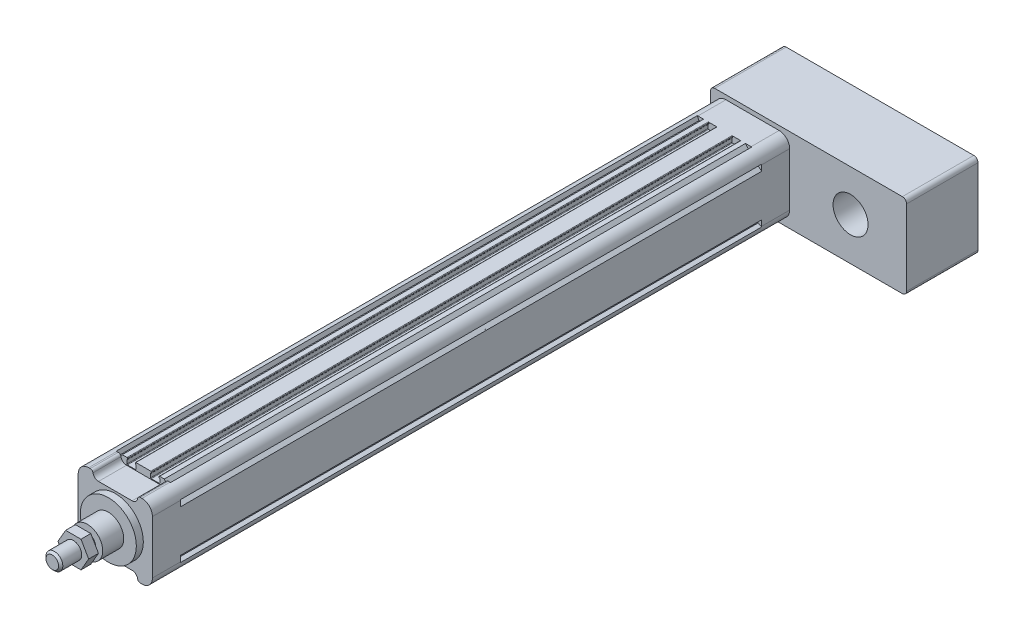
SolidWorks part; units mm, degrees
ref_plane "Front" through (0, 0, 0) normal (0, 0, 1) x (1, 0, 0)
ref_plane "Top" through (0, 0, 0) normal (0, 1, 0) x (1, 0, 0)
ref_plane "Right" through (0, 0, 0) normal (1, 0, 0) x (0, 0, -1)
sketch "草图1" plane through (0, 0, 0) normal (0, 0, 1) x (1, 0, 0)
  line L0 (19.7737, 3) -> (23.3, 3)
  line L1 (23.3, 3) -> (23.3, -3)
  line L2 (23.3, -3) -> (19.7737, -3)
  line L3 (-19.7737, -3) -> (-23.3, -3)
  line L4 (-23.3, -3) -> (-23.3, 3)
  line L5 (-23.3, 3) -> (-19.7737, 3)
  line L6 (-18.2, 24) -> (-19.4434, 26.4869)
  line L7 (-26.4869, 19.4434) -> (-24, 18.2)
  line L8 (-24, 18.2) -> (-24, 17.1)
  line L9 (-24, 17.1) -> (-26.5, 15)
  line L10 (-26.5, 15) -> (-26.5, -15)
  line L11 (-26.5, -15) -> (-24, -17.1)
  line L12 (-24, -17.1) -> (-24, -18.2)
  line L13 (-24, -18.2) -> (-26.4869, -19.4434)
  line L14 (-19.4434, -26.4869) -> (-18.2, -24)
  line L15 (-18.2, -24) -> (-17.1, -24)
  line L16 (-17.1, -24) -> (-15, -26.5)
  line L17 (-15, -26.5) -> (-11.65, -26.5)
  line L18 (-11.25, -26.1) -> (-11.25, -25.6)
  line L19 (-11.65, -25.2) -> (-11.75, -25.2)
  line L20 (-11.75, -25.2) -> (-11.75, -22.4)
  line L21 (-11.35, -22) -> (-5.65, -22)
  line L22 (-5.25, -22.4) -> (-5.25, -25.2)
  line L23 (-5.25, -25.2) -> (-5.35, -25.2)
  line L24 (-5.75, -25.6) -> (-5.75, -26.1)
  line L25 (-5.35, -26.5) -> (5.35, -26.5)
  line L26 (5.75, -26.1) -> (5.75, -25.6)
  line L27 (5.35, -25.2) -> (5.25, -25.2)
  line L28 (5.25, -25.2) -> (5.25, -22.4)
  line L29 (5.65, -22) -> (11.35, -22)
  line L30 (11.75, -22.4) -> (11.75, -25.2)
  line L31 (11.75, -25.2) -> (11.65, -25.2)
  line L32 (11.25, -25.6) -> (11.25, -26.1)
  line L33 (11.65, -26.5) -> (15, -26.5)
  line L34 (15, -26.5) -> (17.1, -24)
  line L35 (17.1, -24) -> (18.2, -24)
  line L36 (18.2, -24) -> (19.4434, -26.4869)
  line L37 (26.4869, -19.4434) -> (24, -18.2)
  line L38 (24, -18.2) -> (24, -17.1)
  line L39 (24, -17.1) -> (26.5, -15)
  line L40 (26.5, -15) -> (26.5, 15)
  line L41 (26.5, 15) -> (24, 17.1)
  line L42 (24, 17.1) -> (24, 18.2)
  line L43 (24, 18.2) -> (26.4869, 19.4434)
  line L44 (19.4434, 26.4869) -> (18.2, 24)
  line L45 (18.2, 24) -> (17.1, 24)
  line L46 (17.1, 24) -> (15, 26.5)
  line L47 (15, 26.5) -> (11.65, 26.5)
  line L48 (11.25, 26.1) -> (11.25, 25.6)
  line L49 (11.65, 25.2) -> (11.75, 25.2)
  line L50 (11.75, 25.2) -> (11.75, 22.4)
  line L51 (11.35, 22) -> (5.65, 22)
  line L52 (5.25, 22.4) -> (5.25, 25.2)
  line L53 (5.25, 25.2) -> (5.35, 25.2)
  line L54 (5.75, 25.6) -> (5.75, 26.1)
  line L55 (5.35, 26.5) -> (-5.35, 26.5)
  line L56 (-5.75, 26.1) -> (-5.75, 25.6)
  line L57 (-5.35, 25.2) -> (-5.25, 25.2)
  line L58 (-5.25, 25.2) -> (-5.25, 22.4)
  line L59 (-5.65, 22) -> (-11.35, 22)
  line L60 (-11.75, 22.4) -> (-11.75, 25.2)
  line L61 (-11.75, 25.2) -> (-11.65, 25.2)
  line L62 (-11.25, 25.6) -> (-11.25, 26.1)
  line L63 (-11.65, 26.5) -> (-15, 26.5)
  line L64 (-15, 26.5) -> (-17.1, 24)
  line L65 (-17.1, 24) -> (-18.2, 24)
  arc A0 (19.7737, 3) -> (-19.7737, 3) centre (0, 0) ccw
  arc A1 (-19.7737, -3) -> (19.7737, -3) centre (0, 0) ccw
  circle A2 centre (19, 19) radius 2.1
  circle A3 centre (19, -19) radius 2.1
  circle A4 centre (-19, -19) radius 2.1
  circle A5 centre (-19, 19) radius 2.1
  arc A6 (-19.4434, 26.4869) -> (-26.4869, 19.4434) centre (-19, 19) ccw
  arc A7 (-26.4869, -19.4434) -> (-19.4434, -26.4869) centre (-19, -19) ccw
  arc A8 (-11.65, -26.5) -> (-11.25, -26.1) centre (-11.65, -26.1) ccw
  arc A9 (-11.25, -25.6) -> (-11.65, -25.2) centre (-11.65, -25.6) ccw
  arc A10 (-11.35, -22) -> (-11.75, -22.4) centre (-11.35, -22.4) ccw
  arc A11 (-5.25, -22.4) -> (-5.65, -22) centre (-5.65, -22.4) ccw
  arc A12 (-5.35, -25.2) -> (-5.75, -25.6) centre (-5.35, -25.6) ccw
  arc A13 (-5.75, -26.1) -> (-5.35, -26.5) centre (-5.35, -26.1) ccw
  arc A14 (5.35, -26.5) -> (5.75, -26.1) centre (5.35, -26.1) ccw
  arc A15 (5.75, -25.6) -> (5.35, -25.2) centre (5.35, -25.6) ccw
  arc A16 (5.65, -22) -> (5.25, -22.4) centre (5.65, -22.4) ccw
  arc A17 (11.75, -22.4) -> (11.35, -22) centre (11.35, -22.4) ccw
  arc A18 (11.65, -25.2) -> (11.25, -25.6) centre (11.65, -25.6) ccw
  arc A19 (11.25, -26.1) -> (11.65, -26.5) centre (11.65, -26.1) ccw
  arc A20 (19.4434, -26.4869) -> (26.4869, -19.4434) centre (19, -19) ccw
  arc A21 (26.4869, 19.4434) -> (19.4434, 26.4869) centre (19, 19) ccw
  arc A22 (11.65, 26.5) -> (11.25, 26.1) centre (11.65, 26.1) ccw
  arc A23 (11.25, 25.6) -> (11.65, 25.2) centre (11.65, 25.6) ccw
  arc A24 (11.35, 22) -> (11.75, 22.4) centre (11.35, 22.4) ccw
  arc A25 (5.25, 22.4) -> (5.65, 22) centre (5.65, 22.4) ccw
  arc A26 (5.35, 25.2) -> (5.75, 25.6) centre (5.35, 25.6) ccw
  arc A27 (5.75, 26.1) -> (5.35, 26.5) centre (5.35, 26.1) ccw
  arc A28 (-5.35, 26.5) -> (-5.75, 26.1) centre (-5.35, 26.1) ccw
  arc A29 (-5.75, 25.6) -> (-5.35, 25.2) centre (-5.35, 25.6) ccw
  arc A30 (-5.65, 22) -> (-5.25, 22.4) centre (-5.65, 22.4) ccw
  arc A31 (-11.75, 22.4) -> (-11.35, 22) centre (-11.35, 22.4) ccw
  arc A32 (-11.65, 25.2) -> (-11.25, 25.6) centre (-11.65, 25.6) ccw
  arc A33 (-11.25, 26.1) -> (-11.65, 26.5) centre (-11.65, 26.1) ccw
extrude "凸台-拉伸1" add sketch "草图1" along normal blind 415
sketch "草图6" plane through (0, 0, 415) normal (0, 0, 1) x (1, 0, 0)
  line L0 (0, 0) -> (19, 0) construction
  line L2 (-26.5, -19) -> (-26.5, 19)
  line L3 (-19, 26.5) -> (-17.9161, 26.5)
  line L4 (26.5, -19) -> (26.5, 19)
  line L5 (-26.5, -26.5) -> (26.5, 26.5) construction
  line L6 (-26.5, 26.5) -> (26.5, -26.5) construction
  line L7 (-12, 21.5) -> (12, 21.5)
  line L9 (19, 26.5) -> (17.9161, 26.5)
  line L10 (19, -26.5) -> (17.9161, -26.5)
  line L11 (-12, -21.5) -> (12, -21.5)
  line L12 (-19, -26.5) -> (-17.9161, -26.5)
  arc A0 (12, 21.5) -> (15.9441, 24.8333) centre (12, 25.5) ccw
  arc A1 (-15.9441, 24.8333) -> (-12, 21.5) centre (-12, 25.5) ccw
  arc A2 (-15.9441, 24.8333) -> (-17.9161, 26.5) centre (-17.9161, 24.5) ccw
  arc A3 (15.9441, 24.8333) -> (17.9161, 26.5) centre (17.9161, 24.5) cw
  arc A4 (-26.5, -19) -> (-19, -26.5) centre (-19, -19) ccw
  arc A5 (19, -26.5) -> (26.5, -19) centre (19, -19) ccw
  arc A6 (26.5, 19) -> (19, 26.5) centre (19, 19) ccw
  arc A7 (-26.5, 19) -> (-19, 26.5) centre (-19, 19) cw
  arc A8 (15.9441, -24.8333) -> (17.9161, -26.5) centre (17.9161, -24.5) ccw
  arc A9 (12, -21.5) -> (15.9441, -24.8333) centre (12, -25.5) cw
  arc A10 (-15.9441, -24.8333) -> (-12, -21.5) centre (-12, -25.5) cw
  arc A11 (-15.9441, -24.8333) -> (-17.9161, -26.5) centre (-17.9161, -24.5) cw
  point P0 (0, 0)
  point P9 (0, 21.5)
  point P13 (20, 20.8461)
  point P16 (-12, 20.8461)
  dimension "D5" = 4
  dimension "D6" = 2
  dimension "D7" = 2
  dimension "D9" = 7.5
  dimension "D1" = 53
  dimension "D2" = 53
  dimension "D3" = 26.5
  dimension "D4" = 24
  dimension "D8" = 5
extrude "凸台-拉伸2" add sketch "草图6" along normal blind 20
sketch "草图7" plane through (0, 0, 435) normal (0, 0, 1) x (1, 0, 0)
  circle A0 centre (0, 0) radius 20
  dimension "D1" = 40
extrude "凸台-拉伸3" add sketch "草图7" along normal blind 5
sketch "草图9" plane through (0, 0, 440) normal (0, 0, 1) x (1, 0, 0)
  circle A0 centre (0, 0) radius 11
  dimension "D1" = 22
extrude "凸台-拉伸4" add sketch "草图9" along normal blind 15
sketch "草图10" plane through (0, 0, 455) normal (0, 0, 1) x (1, 0, 0)
  circle A0 centre (0, 0) radius 6
  dimension "D1" = 12
extrude "凸台-拉伸5" add sketch "草图10" along normal blind 25
sketch "草图11" plane through (0, 0, 0) normal (0, 0, -1) x (-1, 0, 0)
  line L1 (-19, -26.5) -> (19, -26.5)
  line L2 (-26.5, -19) -> (-26.5, 19)
  line L3 (-19, 26.5) -> (19, 26.5)
  line L4 (26.5, -19) -> (26.5, 19)
  line L5 (-26.5, -26.5) -> (26.5, 26.5) construction
  line L6 (-26.5, 26.5) -> (26.5, -26.5) construction
  arc A0 (-26.5, -19) -> (-19, -26.5) centre (-19, -19) ccw
  arc A1 (19, -26.5) -> (26.5, -19) centre (19, -19) ccw
  arc A2 (26.5, 19) -> (19, 26.5) centre (19, 19) ccw
  arc A3 (-26.5, 19) -> (-19, 26.5) centre (-19, 19) cw
  point P0 (0, 0)
  dimension "D3" = 7.5
  dimension "D1" = 53
  dimension "D2" = 53
extrude "凸台-拉伸6" add sketch "草图11" along normal blind 20
sketch "草图12" plane through (0, 0, -20) normal (0, 0, -1) x (-1, 0, 0)
  line L1 (-107, -30.4042) -> (27, -30.4042)
  line L2 (-110, -27.4042) -> (-110, 26.5958)
  line L3 (-107, 29.5958) -> (27, 29.5958)
  line L4 (30, -27.4042) -> (30, 26.5958)
  line L5 (-110, -30.4042) -> (30, 29.5958) construction
  line L6 (-110, 29.5958) -> (30, -30.4042) construction
  arc A0 (27, 29.5958) -> (30, 26.5958) centre (27, 26.5958) cw
  arc A1 (30, -27.4042) -> (27, -30.4042) centre (27, -27.4042) cw
  arc A2 (-110, -27.4042) -> (-107, -30.4042) centre (-107, -27.4042) ccw
  arc A3 (-110, 26.5958) -> (-107, 29.5958) centre (-107, 26.5958) cw
  point P0 (-40, -0.4042)
  dimension "D4" = 3
  dimension "D1" = 60
  dimension "D2" = 140
  dimension "D3" = 30
extrude "凸台-拉伸7" add sketch "草图12" along normal blind 51
sketch "草图13" plane through (0, 0, -20) normal (0, 0, 1) x (1, 0, 0)
  circle A0 centre (70, 0) radius 12.5
  dimension "D2" = 25
  dimension "D1" = 70
extrude "切除-拉伸2" cut sketch "草图13" against normal blind 30
hole_wizard "M6 螺纹孔1" positions "草图14" profile "草图15" tap size "M6" standard "GB"
sketch "草图14" plane through (0, 0, -71) normal (0, 0, -1) x (-1, 0, 0)
  line L0 (30, -27.4042) -> (30, 26.5958) construction
  point P0 (19, -19)
  dimension "D1" = 11
  dimension "D2" = 19
sketch "草图15" plane through (-19, -19, -71) normal (1, 0, 0) x (0, 1, 0)
  line L0 (0, 0) -> (0, 16.5022)
  line L1 (0, 16.5022) -> (2.5, 15)
  line L2 (2.5, 15) -> (2.5, 0)
  line L5 (2.5, 0) -> (0, 0)
  line L10 (0, 16.5022) -> (-2.5, 15) construction
  line L11 (0, -6.35) -> (0, 107.95) construction
  dimension "螺纹孔钻头直径" = 5
  dimension "螺纹孔钻头深度" = 15
  dimension "导头角度" = 118
cosmetic thread "孔螺蚊线4" parameters "D1"=12, "D2"=6
pattern_linear "阵列(线性)1" count 2 spacing 38 along (0, 1, 0) count 2 spacing 38 along (1, 0, 0) of "M6 螺纹孔1"
hole_wizard "M6 螺纹孔2" positions "草图16" profile "草图17" tap size "M6" standard "GB"
sketch "草图16" plane through (0, 0, -71) normal (0, 0, -1) x (-1, 0, 0)
  circle A1 centre (-19, 19) radius 2.5 construction
  circle A2 centre (-19, -19) radius 2.5 construction
  point P0 (-84, -19)
  point P2 (-84, 19)
  dimension "D3" = 65
  dimension "D1" = 19
  dimension "D2" = 19
  dimension "D4" = 65
sketch "草图17" plane through (84, -19, -71) normal (1, 0, 0) x (0, 1, 0)
  line L0 (0, 0) -> (0, 16.5022)
  line L1 (0, 16.5022) -> (2.5, 15)
  line L2 (2.5, 15) -> (2.5, 0)
  line L5 (2.5, 0) -> (0, 0)
  line L10 (0, 16.5022) -> (-2.5, 15) construction
  line L11 (0, -6.35) -> (0, 107.95) construction
  dimension "螺纹孔钻头直径" = 5
  dimension "螺纹孔钻头深度" = 15
  dimension "导头角度" = 118
cosmetic thread "孔螺蚊线5" parameters "D1"=12, "D2"=6
cosmetic thread "孔螺蚊线6" parameters "D1"=12, "D2"=6
hole_wizard "M6 螺纹孔3" positions "草图19" profile "草图20" tap size "M6" standard "GB"
sketch "草图19" plane through (-26.5, 0, 0) normal (-1, 0, 0) x (0, 0, 1)
  line L0 (435, 19) -> (435, -19) construction
  point P0 (425, 11)
  point P2 (425, -11)
  dimension "D1" = 10
  dimension "D2" = 10
  dimension "D3" = 22
  dimension "D4" = 11
sketch "草图20" plane through (-26.5, 11, 425) normal (0, 1, 0) x (0, 0, 1)
  line L0 (0, 0) -> (0, 16.5022)
  line L1 (0, 16.5022) -> (2.5, 15)
  line L2 (2.5, 15) -> (2.5, 0)
  line L5 (2.5, 0) -> (0, 0)
  line L10 (0, 16.5022) -> (-2.5, 15) construction
  line L11 (0, -6.35) -> (0, 107.95) construction
  dimension "螺纹孔钻头直径" = 5
  dimension "螺纹孔钻头深度" = 15
  dimension "导头角度" = 118
cosmetic thread "孔螺蚊线7" parameters "D1"=12, "D2"=6
cosmetic thread "孔螺蚊线8" parameters "D1"=12, "D2"=6
hole_wizard "M6 螺纹孔4" positions "草图21" profile "草图22" tap size "M6" standard "GB"
sketch "草图21" plane through (-26.5, 0, 0) normal (-1, 0, 0) x (0, 0, 1)
  line L0 (-20, -27.4042) -> (-20, 26.5958) construction
  line L1 (-20, -19) -> (-20, 19) construction
  point P0 (-10, 11)
  point P2 (-10, -11)
  dimension "D1" = 10
  dimension "D2" = 10
  dimension "D3" = 11
  dimension "D4" = 11
sketch "草图22" plane through (-26.5, 11, -10) normal (0, 1, 0) x (0, 0, 1)
  line L0 (0, 0) -> (0, 16.5022)
  line L1 (0, 16.5022) -> (2.5, 15)
  line L2 (2.5, 15) -> (2.5, 0)
  line L5 (2.5, 0) -> (0, 0)
  line L10 (0, 16.5022) -> (-2.5, 15) construction
  line L11 (0, -6.35) -> (0, 107.95) construction
  dimension "螺纹孔钻头直径" = 5
  dimension "螺纹孔钻头深度" = 15
  dimension "导头角度" = 118
cosmetic thread "孔螺蚊线9" parameters "D1"=12, "D2"=6
cosmetic thread "孔螺蚊线10" parameters "D1"=12, "D2"=6
chamfer "倒角1" distance 1.5 angle 45 1 edges at (6, 0, 480)
sketch "草图23" plane through (0, 0, 455) normal (0, 0, 1) x (1, 0, 0)
  line L1 (10.9697, 0) -> (5.4848, 9.5)
  line L2 (5.4848, 9.5) -> (-5.4848, 9.5)
  line L3 (-5.4848, 9.5) -> (-10.9697, 0)
  line L4 (-10.9697, 0) -> (-5.4848, -9.5)
  line L5 (-5.4848, -9.5) -> (5.4848, -9.5)
  line L6 (5.4848, -9.5) -> (10.9697, 0)
  circle A0 centre (0, 0) radius 9.5 construction
  dimension "D1" = 19
extrude "凸台-拉伸8" add sketch "草图23" along normal blind 7 from offset 3
